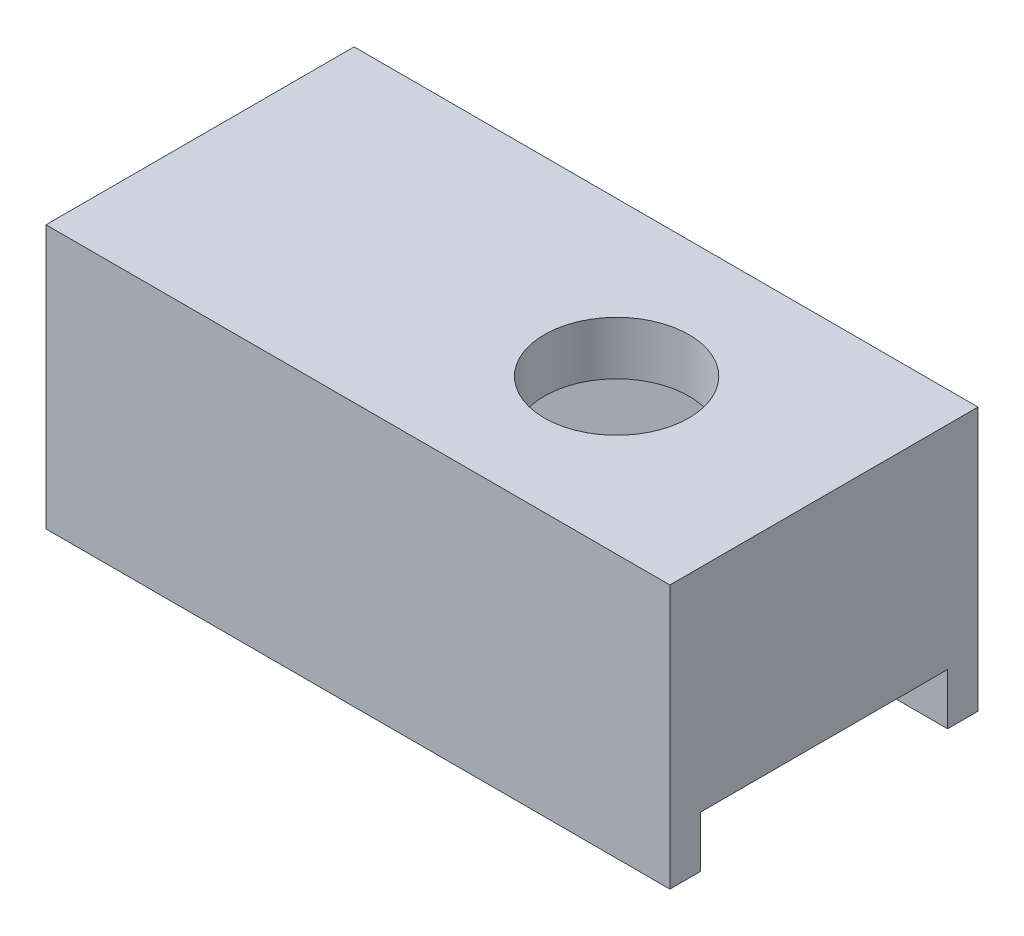
SolidWorks part; units mm, degrees
material "ABS"
ref_plane "Front Plane" through (0, 0, 0) normal (0, 0, 1) x (1, 0, 0)
ref_plane "Top Plane" through (0, 0, 0) normal (0, 1, 0) x (1, 0, 0)
ref_plane "Right Plane" through (0, 0, 0) normal (1, 0, 0) x (0, 0, -1)
sketch "Sketch1" plane through (0, 0, 0) normal (0, 1, 0) x (1, 0, 0)
  line L1 (-16.4, -8.1) -> (16.4, -8.1)
  line L2 (-16.4, -8.1) -> (-16.4, 8.1)
  line L3 (-16.4, 8.1) -> (16.4, 8.1)
  line L4 (16.4, -8.1) -> (16.4, 8.1)
extrude "Boss-Extrude1" add sketch "Sketch1" along normal mid plane 13.85 from offset 12.075
sketch "Sketch2" plane through (0, 0, 0) normal (0, 1, 0) x (1, 0, 0)
  line L0 (-16.4, 8.1) -> (-16.4, -8.1) construction
  line L1 (-16.4, -6.5) -> (16.4, -6.5)
  line L2 (-16.4, -6.5) -> (-16.4, 6.5)
  line L3 (-16.4, 6.5) -> (16.4, 6.5)
  line L4 (16.4, -6.5) -> (16.4, 6.5)
  line L5 (16.4, -8.1) -> (16.4, 8.1) construction
extrude "Cut-Extrude1" cut sketch "Sketch2" against normal mid plane 2.7 from offset 6.5
sketch "Sketch3" plane through (0, 0, 0) normal (0, 1, 0) x (1, 0, 0)
  line L1 (-11.7, -6.5) -> (11.7, -6.5)
  line L2 (-11.7, -6.5) -> (-11.7, 6.5)
  line L3 (-11.7, 6.5) -> (11.7, 6.5)
  line L4 (11.7, -6.5) -> (11.7, 6.5)
extrude "Cut-Extrude2" cut sketch "Sketch3" against normal mid plane 8.35 from offset 12.025
sketch "Sketch4" plane through (0, 0, 0) normal (0, 1, 0) x (1, 0, 0)
  circle A0 centre (5.5, 0) radius 3.8
extrude "Cut-Extrude3" cut sketch "Sketch4" against normal mid plane 2.8 from offset 17.6
sketch "Sketch5" plane through (0, 0, 0) normal (0, 1, 0) x (1, 0, 0)
  circle A0 centre (-13.75, 0) radius 0.925
  circle A1 centre (13.75, 0) radius 0.925
extrude "Cut-Extrude4" cut sketch "Sketch5" against normal mid plane 8.02 from offset 11.84
